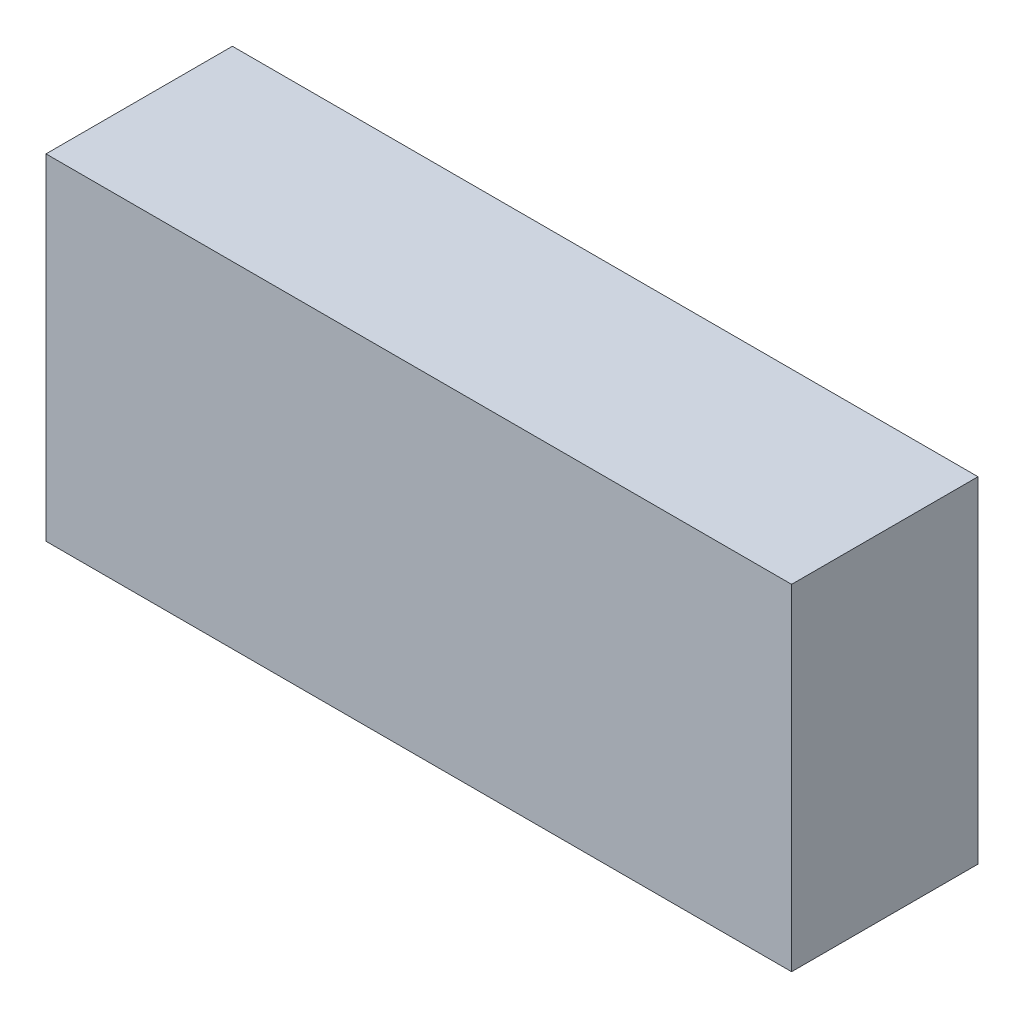
SolidWorks part; units mm, degrees
ref_plane "前视基准面" through (0, 0, 0) normal (0, 0, 1) x (1, 0, 0)
ref_plane "上视基准面" through (0, 0, 0) normal (0, 1, 0) x (1, 0, 0)
ref_plane "右视基准面" through (0, 0, 0) normal (1, 0, 0) x (0, 0, -1)
sketch "草图1" plane through (0, 0, 0) normal (0, 0, 1) x (1, 0, 0)
  line L0 (1, 0.45) -> (1, -0.45)
  line L1 (1, -0.45) -> (-1, -0.45)
  line L2 (-1, -0.45) -> (-1, 0.45)
  line L3 (-1, 0.45) -> (1, 0.45)
extrude "Component_Outline" add sketch "草图1" along normal blind 0.5 separate body
sketch3d "3D草图1"
  line L0 (0, 0, 0) -> (1, 0, 0)
  line L1 (0, 0, 0) -> (0, 1, 0)
  line L2 (0, 0, 0) -> (0, 0, 1)
  point P0 (0, 0, 0)
